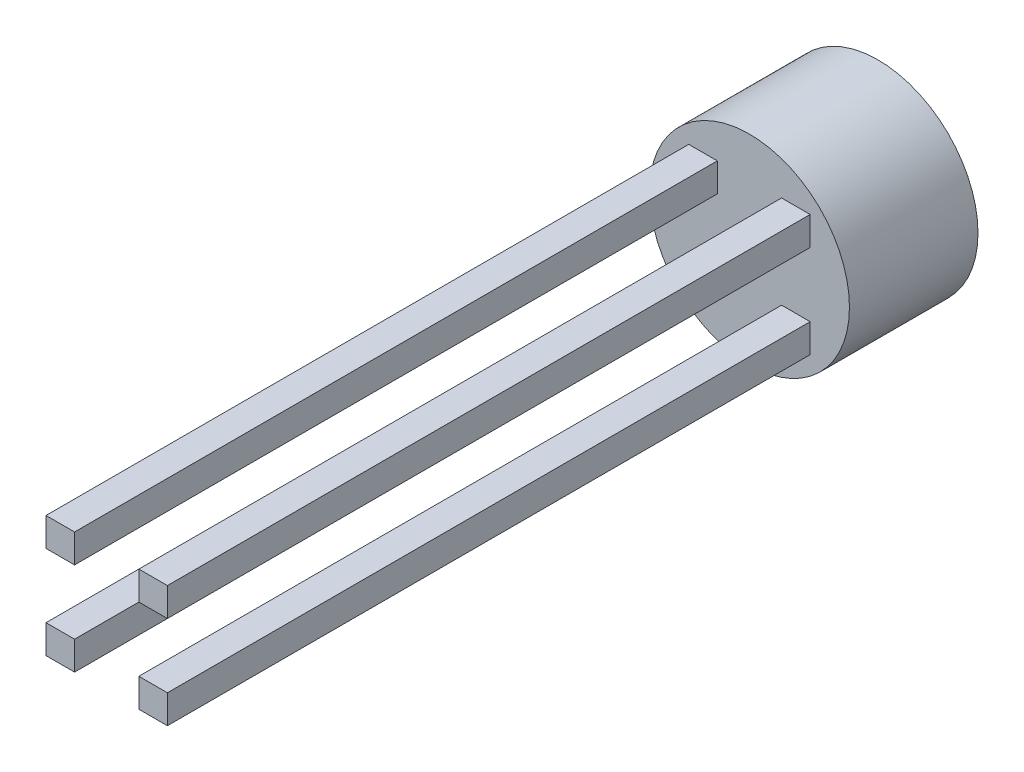
SolidWorks part; units mm, degrees
ref_plane "前视基准面" through (0, 0, 0) normal (0, 0, 1) x (1, 0, 0)
ref_plane "上视基准面" through (0, 0, 0) normal (0, 1, 0) x (1, 0, 0)
ref_plane "右视基准面" through (0, 0, 0) normal (1, 0, 0) x (0, 0, -1)
other "Configuration Table"
sketch "草图1" plane through (0, 0, 0) normal (0, 0, 1) x (1, 0, 0)
  circle A0 centre (0, 0) radius 7
  dimension "D1" = 14
extrude "凸台-拉伸1" add sketch "草图1" along normal blind 9
sketch "草图2" plane through (0, 0, 9) normal (0, 0, 1) x (1, 0, 0)
  line L0 (2.25, 2.25) -> (2.25, 4.25)
  line L1 (-2.25, 2.25) -> (2.25, 2.25) construction
  line L2 (-2.25, 2.25) -> (-2.25, -2.25) construction
  line L3 (-2.25, -2.25) -> (2.25, -2.25) construction
  line L4 (2.25, 2.25) -> (2.25, -2.25) construction
  line L5 (-2.25, 2.25) -> (2.25, -2.25) construction
  line L6 (-2.25, -2.25) -> (2.25, 2.25) construction
  line L7 (-2.25, 2.25) -> (-4.25, 2.25)
  line L8 (-2.25, 2.25) -> (-2.25, 4.25)
  line L9 (-2.25, 4.25) -> (-4.25, 4.25)
  line L10 (-4.25, 2.25) -> (-4.25, 4.25)
  line L11 (2.25, 2.25) -> (4.25, 2.25)
  line L12 (4.25, 2.25) -> (4.25, 4.25)
  line L13 (2.25, 4.25) -> (4.25, 4.25)
  line L14 (2.25, -2.25) -> (4.25, -2.25)
  line L15 (2.25, -2.25) -> (2.25, -4.25)
  line L16 (2.25, -4.25) -> (4.25, -4.25)
  line L17 (4.25, -2.25) -> (4.25, -4.25)
  line L18 (-2.25, -2.25) -> (-2.25, -4.25)
  line L19 (-2.25, -2.25) -> (-4.25, -2.25)
  line L20 (-4.25, -2.25) -> (-4.25, -4.25)
  line L21 (-2.25, -4.25) -> (-4.25, -4.25)
  point P0 (0, 0)
  point P24 (0, 0)
  dimension "D1" = 4.5
  dimension "D2" = 4.5
  dimension "D3" = 2
  dimension "D4" = 2
  dimension "D5" = 4
extrude "凸台-拉伸2" add sketch "草图2" along normal blind 45
sketch "草图3" plane through (0, 0, 0) normal (1, 0, 0) x (0, 0, -1)
  line L0 (0, -0.2561) -> (-16.3734, -0.2561) construction
  line L1 (0, -7) -> (0, 7) construction
sketch "草图4" plane through (0, 0, 0) normal (0, 0, -1) x (-1, 0, 0)
  line L0 (-2.5009, 1.671) -> (-2.95, 1.2219)
  line L9 (3.1931, 0) -> (2.95, 0.5868)
  line L10 (2.2578, 2.2578) -> (1.671, 2.5009)
  line L11 (0, 3.1931) -> (-0.5868, 2.95)
  line L12 (-2.2578, 2.2578) -> (-2.5009, 1.671)
  line L13 (-3.1931, 0) -> (-2.95, -0.5868)
  line L14 (-2.2578, -2.2578) -> (-1.671, -2.5009)
  line L15 (0, -3.1931) -> (0.5868, -2.95)
  line L16 (2.2578, -2.2578) -> (2.5009, -1.671)
  line L17 (1.2219, -2.95) -> (1.671, -2.5009)
  line L18 (2.95, -1.2219) -> (2.95, -0.5868)
  line L19 (2.95, 1.2219) -> (2.5009, 1.671)
  line L20 (1.2219, 2.95) -> (0.5868, 2.95)
  line L21 (-1.2219, 2.95) -> (-1.671, 2.5009)
  line L22 (-2.95, 1.2219) -> (-2.95, 0.5868)
  line L23 (-2.95, -1.2219) -> (-2.5009, -1.671)
  line L24 (-1.2219, -2.95) -> (-0.5868, -2.95)
  line L25 (-1.671, 2.5009) -> (-2.2578, 2.2578)
  line L26 (-0.5868, 2.95) -> (-1.2219, 2.95)
  line L27 (0.5868, 2.95) -> (0, 3.1931)
  line L28 (1.671, 2.5009) -> (1.2219, 2.95)
  line L29 (2.5009, 1.671) -> (2.2578, 2.2578)
  line L30 (2.95, 0.5868) -> (2.95, 1.2219)
  line L31 (2.95, -0.5868) -> (3.1931, 0)
  line L32 (2.5009, -1.671) -> (2.95, -1.2219)
  line L33 (1.671, -2.5009) -> (2.2578, -2.2578)
  line L34 (0.5868, -2.95) -> (1.2219, -2.95)
  line L35 (-0.5868, -2.95) -> (0, -3.1931)
  line L36 (-1.671, -2.5009) -> (-1.2219, -2.95)
  line L37 (-2.5009, -1.671) -> (-2.2578, -2.2578)
  line L38 (-2.95, -0.5868) -> (-2.95, -1.2219)
  line L39 (-2.95, 0.5868) -> (-3.1931, 0)
  arc A2 (2.086, -2.086) -> (1.1289, -2.7254) centre (0, 0) ccw construction
  circle A3 centre (0, 0) radius 2.95 construction
  dimension "D1" = 5.9
  dimension "D2" = 5.9
extrude "切除-拉伸1" cut sketch "草图4" against normal blind 4
sketch "草图5" plane through (0, 0, 4) normal (0, 0, -1) x (-1, 0, 0)
  line L1 (-1, 1) -> (1, 1)
  line L2 (-1, 1) -> (-1, -1)
  line L3 (-1, -1) -> (1, -1)
  line L4 (1, 1) -> (1, -1)
  line L5 (-1, 1) -> (1, -1) construction
  line L6 (-1, -1) -> (1, 1) construction
  point P0 (0, 0)
  dimension "D1" = 2
  dimension "D2" = 2
extrude "凸台-拉伸3" add sketch "草图5" along normal up to surface (4 mm away) up to face at (0, 0, 0)
